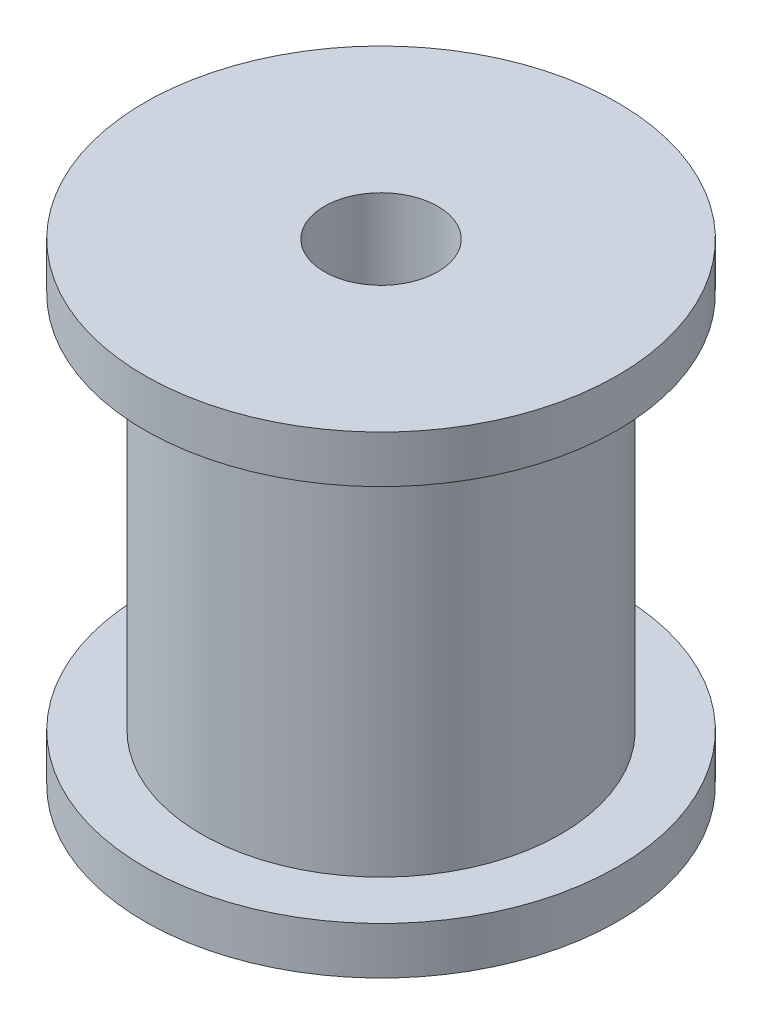
SolidWorks part; units mm, degrees
material "三聚氰胺甲醛树脂"
ref_plane "前视基准面" through (0, 0, 0) normal (0, 0, 1) x (1, 0, 0)
ref_plane "上视基准面" through (0, 0, 0) normal (0, 1, 0) x (1, 0, 0)
ref_plane "右视基准面" through (0, 0, 0) normal (1, 0, 0) x (0, 0, -1)
sketch "草图1" plane through (0, 0, 0) normal (0, 0, 1) x (1, 0, 0)
  line L0 (0, -219.7338) -> (0, 10766.9558) construction
  line L1 (-219.7338, 0) -> (10766.9558, 0) construction
  line L2 (3, -12.5) -> (3, 12.5)
  line L3 (3, 12.5) -> (12.5, 12.5)
  line L4 (12.5, 12.5) -> (12.5, 10)
  line L5 (12.5, 10) -> (9.5, 10)
  line L6 (9.5, 10) -> (9.5, -10)
  line L7 (12.5, -10) -> (9.5, -10)
  line L8 (12.5, -12.5) -> (12.5, -10)
  line L9 (3, -12.5) -> (12.5, -12.5)
  point P12 (9.5, 0)
  point P15 (3, 0)
  dimension "D1" = 6
  dimension "D2" = 19
  dimension "D3" = 3
  dimension "D4" = 20
  dimension "D5" = 25
revolve "旋转1" add sketch "草图1" angle 360 about L0
